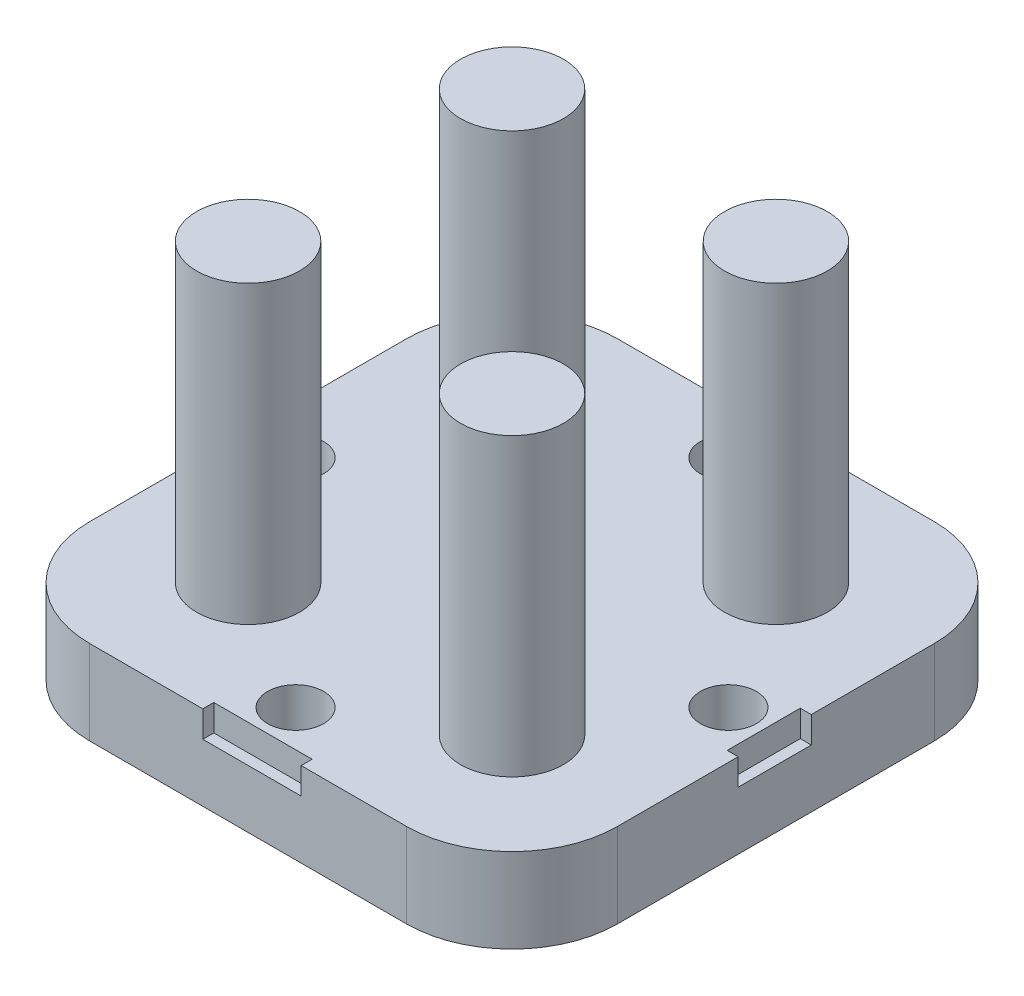
SolidWorks part; units mm, degrees
ref_plane "Alzado" through (0, 0, 0) normal (0, 0, 1) x (1, 0, 0)
ref_plane "Planta" through (0, 0, 0) normal (0, 1, 0) x (1, 0, 0)
ref_plane "Vista lateral" through (0, 0, 0) normal (1, 0, 0) x (0, 0, -1)
sketch "Croquis1" plane through (0, 0, 0) normal (0, 1, 0) x (1, 0, 0)
  line L0 (-14.4792, 25.9114) -> (15.5208, 25.9114)
  line L1 (-24.4792, 15.9114) -> (-24.4792, -14.0886)
  line L2 (-14.4792, -24.0886) -> (15.5208, -24.0886)
  line L3 (25.5208, 15.9114) -> (25.5208, -14.0886)
  line L4 (-24.4792, 25.9114) -> (25.5208, -24.0886) construction
  line L5 (-24.4792, -24.0886) -> (25.5208, 25.9114) construction
  arc A0 (-24.4792, -14.0886) -> (-14.4792, -24.0886) centre (-14.4792, -14.0886) ccw
  arc A1 (25.5208, -14.0886) -> (15.5208, -24.0886) centre (15.5208, -14.0886) cw
  arc A2 (15.5208, 25.9114) -> (25.5208, 15.9114) centre (15.5208, 15.9114) cw
  arc A3 (-14.4792, 25.9114) -> (-24.4792, 15.9114) centre (-14.4792, 15.9114) ccw
  point P0 (0.5208, 0.9114)
  dimension "D3" = 10
  dimension "D1" = 50
  dimension "D2" = 50
extrude "Saliente-Extruir1" add sketch "Croquis1" along normal blind 8
sketch "Croquis2" plane through (0, 8, 0) normal (0, 1, 0) x (1, 0, 0)
  line L0 (15.5208, 25.9114) -> (-14.4792, 25.9114) construction
  line L2 (-24.4792, 15.9114) -> (-24.4792, -14.0886) construction
  circle A1 centre (-11.9792, 13.4114) radius 4.875
  dimension "D2" = 9.75
  dimension "D3" = 12.5
  dimension "D4" = 12.5
extrude "Saliente-Extruir2" add sketch "Croquis2" along normal blind 28
pattern_linear "MatrizL1" count 2 spacing 25 along (1, 0, 0) count 2 spacing 25 along (0, 0, 1) of "Saliente-Extruir2"
sketch "Croquis3" plane through (0, 8, 0) normal (0, 1, 0) x (1, 0, 0)
  circle A5 centre (0.5208, 0.9114) radius 2.65
  circle A6 centre (0.5208, 21.4114) radius 2.65
  circle A7 centre (0.5208, -19.5886) radius 2.65
  circle A8 centre (-19.9792, 0.9114) radius 2.65
  circle A9 centre (21.0208, 0.9114) radius 2.65
  dimension "D1" = 5.3
  dimension "D3" = 5.3
  dimension "D4" = 5.3
  dimension "D2" = 5.3
  dimension "D5" = 5.3
extrude "Cortar-Extruir1" cut sketch "Croquis3" against normal blind 5.3
sketch "Croquis4" plane through (0, 8, 0) normal (0, 1, 0) x (1, 0, 0)
  line L0 (15.5208, 25.9114) -> (-14.4792, 25.9114) construction
  line L1 (-3.7674, 25.9114) -> (5.546, 25.9114)
  line L2 (-3.7674, 25.9114) -> (-3.7674, 24.687)
  line L3 (5.546, 23.0487) -> (5.5584, 23.0487)
  line L4 (5.546, 25.9114) -> (5.546, 24.687)
  line L9 (0, 0) -> (-3.7674, 0) construction
  line L10 (5.546, -25.9114) -> (5.546, -23.0487)
  line L11 (-3.7674, -23.0487) -> (5.546, -23.0487)
  line L12 (-3.7674, -25.9114) -> (-3.7674, -23.0487)
  line L13 (-3.7674, -25.9114) -> (5.546, -25.9114)
  line L14 (0, 0) -> (0, -5.8238) construction
  line L15 (-24.4792, 15.9114) -> (-24.4792, -14.0886) construction
  line L16 (-24.4792, 4.2604) -> (-26.6683, 4.2604)
  line L18 (-24.4792, -2.6623) -> (-26.6683, -2.6623)
  line L19 (-26.6683, 4.2604) -> (-26.6683, -2.6623)
  line L20 (26.6683, 4.2604) -> (26.6683, -2.6623)
  line L21 (24.4792, -2.6623) -> (26.6683, -2.6623)
  line L22 (24.4792, 4.2604) -> (24.4792, -2.6623)
  line L23 (24.4792, 4.2604) -> (26.6683, 4.2604)
  line L25 (-24.4792, 4.2604) -> (-23.2621, 4.2604)
  line L27 (-24.4792, -2.6623) -> (-23.2621, -2.6623)
  line L28 (-23.2621, 4.2604) -> (-23.2621, -2.6623)
  line L29 (-3.7674, 25.9114) -> (5.546, 25.9114)
  line L30 (-3.7674, 25.9114) -> (-3.7674, 24.687)
  line L31 (-3.7674, 24.687) -> (5.546, 24.687)
  line L32 (5.546, 25.9114) -> (5.546, 24.687)
  line M31 (25.5208, -14.0886) -> (25.5208, 15.9114)
  line M32 (15.5208, 25.9114) -> (-14.4792, 25.9114)
  line M34 (-14.4792, -24.0886) -> (15.5208, -24.0886)
extrude "Cortar-Extruir2" cut sketch "Croquis4" against normal blind 2.5 contours L12 L13 L10 M34 | L12 L10 L11 M34 | L23 L22 L21 M31 | L2 L31 L4 M32 | L19 L18 L27 L28 L25 L16
